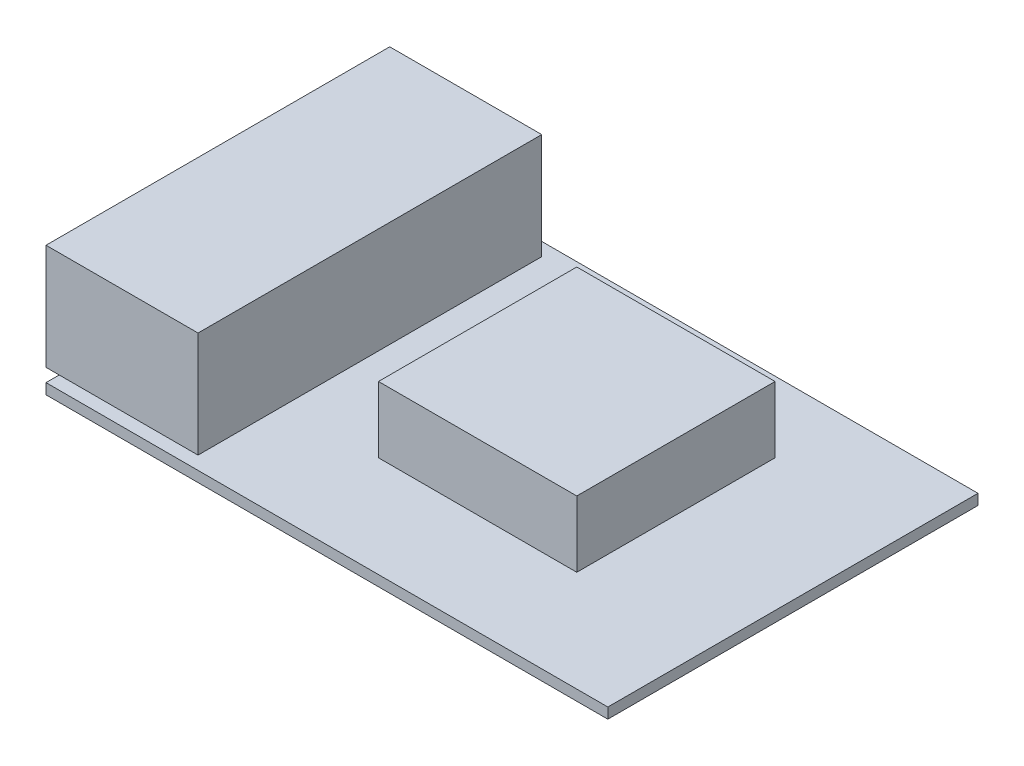
SolidWorks part; units mm, degrees
ref_plane "Front Plane" through (0, 0, 0) normal (0, 0, 1) x (1, 0, 0)
ref_plane "Top Plane" through (0, 0, 0) normal (0, 1, 0) x (1, 0, 0)
ref_plane "Right Plane" through (0, 0, 0) normal (1, 0, 0) x (0, 0, -1)
ref_plane "PZm18" through (0, -18, 0) normal (0, 1, 0) x (1, 0, 0)
sketch "Sketch1" plane through (0, -18, 0) normal (0, 1, 0) x (1, 0, 0)
  line L0 (-40, -82.3) -> (45, -82.3)
  line L1 (45, -82.3) -> (45, -26.3)
  line L2 (45, -26.3) -> (-40, -26.3)
  line L3 (-40, -26.3) -> (-40, -82.3)
extrude "Pi 4 PCB" add sketch "Sketch1" along normal blind 1.6
ref_plane "PZm16_4" through (0, -16.4, 0) normal (0, 1, 0) x (1, 0, 0)
sketch "Sketch2" plane through (0, -16.4, 0) normal (0, 1, 0) x (1, 0, 0)
  line L0 (-42, -80.3) -> (-19, -80.3)
  line L1 (-19, -80.3) -> (-19, -28.3)
  line L2 (-19, -28.3) -> (-42, -28.3)
  line L3 (-42, -28.3) -> (-42, -80.3)
extrude "USB And Ethernet" add sketch "Sketch2" along normal blind 16
ref_plane "PZm10_4" through (0, -10.4, 0) normal (0, 1, 0) x (1, 0, 0)
sketch "Sketch3" plane through (0, -10.4, 0) normal (0, 1, 0) x (1, 0, 0)
  line L0 (1, -73) -> (31, -73)
  line L1 (31, -73) -> (31, -43)
  line L2 (31, -43) -> (1, -43)
  line L3 (1, -43) -> (1, -73)
extrude "Fan" add sketch "Sketch3" along normal blind 10
